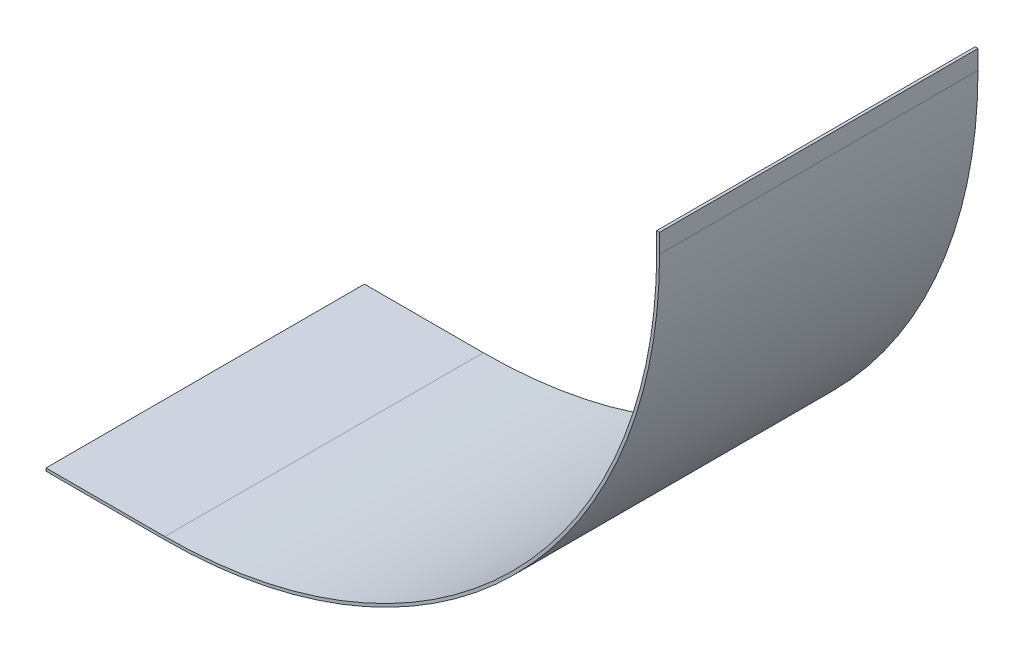
SolidWorks part; units mm, degrees
ref_plane "Front Plane" through (0, 0, 0) normal (0, 0, 1) x (1, 0, 0)
ref_plane "Top Plane" through (0, 0, 0) normal (0, 1, 0) x (1, 0, 0)
ref_plane "Right Plane" through (0, 0, 0) normal (1, 0, 0) x (0, 0, -1)
sketch "Sketch1" plane through (0, 0, 0) normal (0, 0, 1) x (1, 0, 0)
  line L0 (1200, -5485) -> (950, -5485)
  line L1 (1200, -5485) -> (700, -5485) construction
  line L2 (2235, -4410) -> (2235, -4450)
  line L3 (2205, -4410) -> (2295, -4410) construction
  line L4 (2235, -4450) -> (2235, -4410) construction
  arc A0 (1200, -5485) -> (2235, -4450) centre (1200, -4450) ccw construction
  arc A1 (1200, -5485) -> (2235, -4450) centre (1200, -4450) ccw
extrude "Extrude-Thin1" add sketch "Sketch1" against normal up to vertex (670 mm away) thin thin type one direction reverse wall 6
